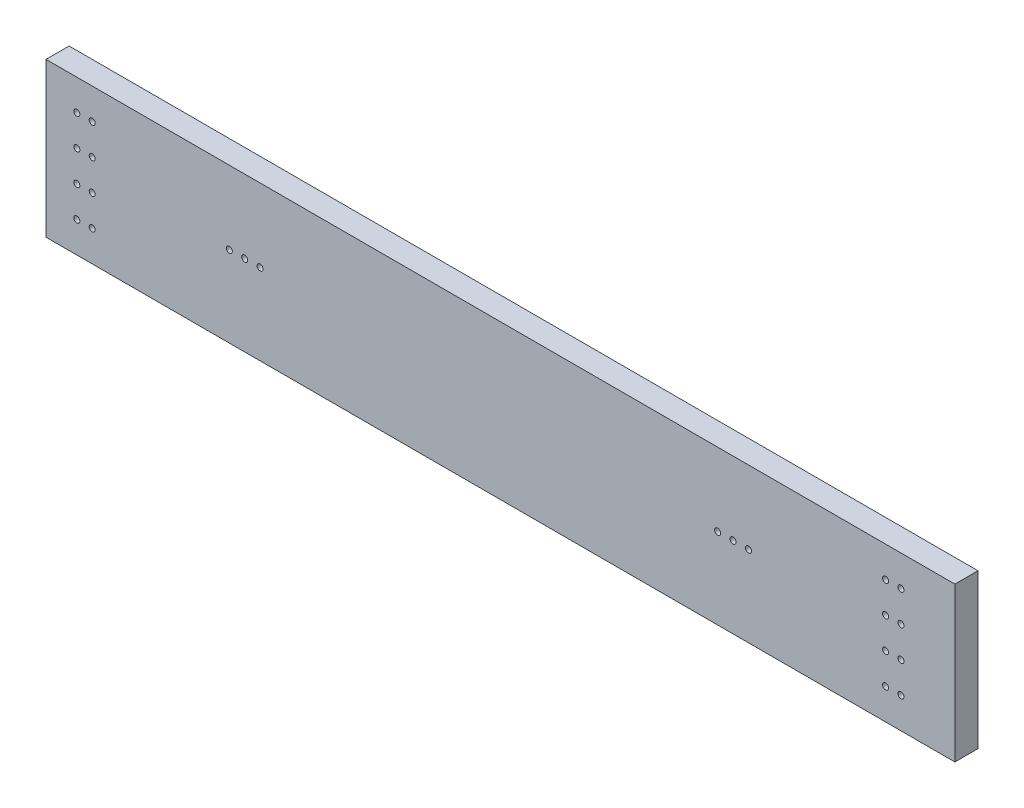
SolidWorks part; units mm, degrees
material "Pine"
ref_plane "Front Plane" through (0, 0, 0) normal (0, 0, 1) x (1, 0, 0)
ref_plane "Top Plane" through (0, 0, 0) normal (0, 1, 0) x (1, 0, 0)
ref_plane "Right Plane" through (0, 0, 0) normal (1, 0, 0) x (0, 0, -1)
sketch "Sketch1" plane through (0, 0, 0) normal (0, 0, 1) x (1, 0, 0)
  line L1 (0, 0) -> (749.3, 0)
  line L2 (0, 0) -> (0, 127)
  line L3 (0, 127) -> (749.3, 127)
  line L4 (749.3, 0) -> (749.3, 127)
  dimension "D1" = 127
  dimension "D2" = 749.3
extrude "Boss-Extrude1" add sketch "Sketch1" along normal mid plane 19.05
sketch "Sketch2" plane through (0, 0, 9.525) normal (0, 0, 1) x (1, 0, 0)
  line L0 (749.3, 127) -> (0, 127) construction
  line L1 (749.3, 127) -> (0, 127) construction
  line L2 (730.25, 127) -> (730.25, 0) construction
  line L3 (0, 127) -> (749.3, 127) construction
  line L4 (374.65, 127) -> (374.65, 0) construction
  line L5 (0, 0) -> (749.3, 0) construction
  line L6 (749.3, 0) -> (749.3, 127) construction
  line L8 (749.3, 0) -> (749.3, 127) construction
  line L9 (0, 127) -> (0, 0) construction
  circle A29 centre (566.42, 66.675) radius 2.4892
  circle A30 centre (553.72, 66.675) radius 2.4892
  circle A31 centre (163.83, 66.675) radius 2.4892
  circle A32 centre (176.53, 66.675) radius 2.4892
  circle A33 centre (579.12, 66.675) radius 2.4892
  circle A34 centre (151.13, 66.675) radius 2.4892
  circle A35 centre (692.15, 101.6) radius 2.4892
  circle A36 centre (704.85, 101.6) radius 2.4892
  circle A37 centre (704.85, 76.2) radius 2.4892
  circle A38 centre (704.85, 50.8) radius 2.4892
  circle A39 centre (704.85, 25.4) radius 2.4892
  circle A40 centre (692.15, 76.2) radius 2.4892
  circle A41 centre (692.15, 50.8) radius 2.4892
  circle A42 centre (692.15, 25.4) radius 2.4892
  circle A43 centre (25.4, 101.6) radius 2.4892
  circle A44 centre (38.1, 101.6) radius 2.4892
  circle A45 centre (38.1, 76.2) radius 2.4892
  circle A46 centre (38.1, 50.8) radius 2.4892
  circle A47 centre (38.1, 25.4) radius 2.4892
  circle A48 centre (25.4, 76.2) radius 2.4892
  circle A49 centre (25.4, 50.8) radius 2.4892
  circle A50 centre (25.4, 25.4) radius 2.4892
  point P36 (0, 0)
  dimension "D1" = 4.9784
  dimension "D2" = 179.07
  dimension "D3" = 355.6
  dimension "D4" = 60.325
  dimension "D5" = 12.7
  dimension "D8" = 198.12
  dimension "D9" = 60.325
  dimension "D10" = 19.05
  dimension "D11" = 12.7
  dimension "D12" = 12.7
  dimension "D13" = 2
  dimension "D14" = 4
  dimension "D15" = 12.7
  dimension "D16" = 25.4
  dimension "D17" = 4.9784
  dimension "D18" = 25.4
  dimension "D19" = 44.45
  dimension "D20" = 2
  dimension "D6" = 4.9784
  dimension "D7" = 12.7
  dimension "D22" = 4.9784
  dimension "D23" = 12.7
  dimension "D24" = 25.4
  dimension "D25" = 25.4
  dimension "D26" = 25.4
  dimension "D21" = 4
extrude "Cut-Extrude1" cut sketch "Sketch2" against normal through all
